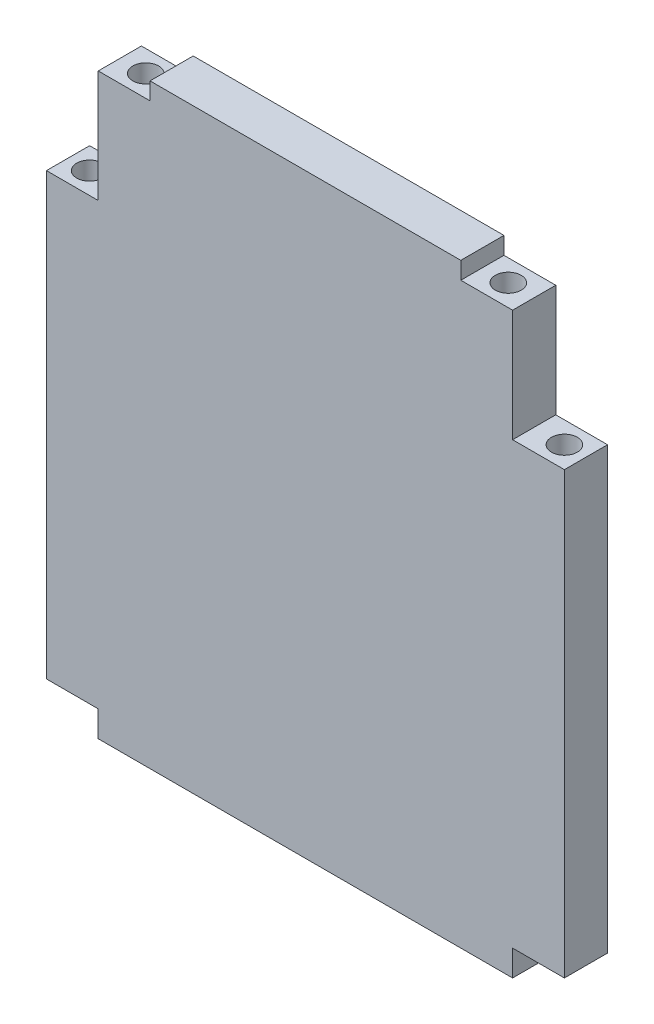
SolidWorks part; units mm, degrees
material "5052-O"
ref_plane "正面" through (0, 0, 0) normal (0, 0, 1) x (1, 0, 0)
ref_plane "平面" through (0, 0, 0) normal (0, 1, 0) x (1, 0, 0)
ref_plane "右側面" through (0, 0, 0) normal (1, 0, 0) x (0, 0, -1)
sketch "ｽｹｯﾁ1" plane through (0, 0, 0) normal (0, 0, 1) x (1, 0, 0)
  line L0 (-30, 0) -> (30, 0) construction
  line L1 (30, -25.5) -> (-30, -25.5) construction
  line L2 (30, -25.5) -> (30, 25.5)
  line L3 (30, 25.5) -> (-30, 25.5) construction
  line L4 (-30, -25.5) -> (-30, 25.5)
  line L5 (30, -25.5) -> (-30, 25.5) construction
  line L6 (30, 25.5) -> (-30, -25.5) construction
  line L7 (-30, 25.5) -> (-24, 25.5)
  line L8 (-24, 25.5) -> (-24, 38.5)
  line L9 (-24, 38.5) -> (-18, 38.5)
  line L10 (24, 38.5) -> (24, 25.5)
  line L11 (24, 25.5) -> (30, 25.5)
  line L12 (-30, -25.5) -> (-24, -25.5)
  line L13 (-24, -25.5) -> (-24, -28.5)
  line L14 (-24, -28.5) -> (24, -28.5)
  line L15 (24, -28.5) -> (24, -25.5)
  line L16 (24, -25.5) -> (30, -25.5)
  line L17 (-18, 38.5) -> (-18, 40.5)
  line L18 (-18, 40.5) -> (18, 40.5)
  line L19 (18, 40.5) -> (18, 38.5)
  line L20 (18, 38.5) -> (24, 38.5)
  point P0 (0, 0)
  dimension "D1" = 60
  dimension "D2" = 51
  dimension "D3" = 13
  dimension "D4" = 6
  dimension "D5" = 3
  dimension "D6" = 2
extrude "ﾎﾞｽ - 押し出し1" add sketch "ｽｹｯﾁ1" along normal blind 5
sketch "ｽｹｯﾁ2" plane through (0, 25.5, 0) normal (0, 1, 0) x (1, 0, 0)
  line L0 (-30, -2.5) -> (30, -2.5) construction
  line L1 (-30, -5) -> (-30, 0) construction
  line L2 (30, -5) -> (30, 0) construction
  line L3 (18, -5) -> (-18, -5) construction
  line L4 (0, 0) -> (0, -5) construction
  circle A0 centre (-27.5, -2.5) radius 1.5
  circle A1 centre (27.5, -2.5) radius 1.5
  dimension "D1" = 2.5
  dimension "D2" = 3
extrude "ｶｯﾄ - 押し出し1" cut sketch "ｽｹｯﾁ2" against normal blind 10
mirror "ﾐﾗｰ1" about plane through (0, 0, 0) normal (0, 1, 0) of "ｶｯﾄ - 押し出し1"
sketch "ｽｹｯﾁ3" plane through (0, 38.5, 0) normal (0, 1, 0) x (1, 0, 0)
  line L0 (-24, 0) -> (-18, -5) construction
  line L2 (18, 0) -> (-18, 0) construction
  line L3 (0, 0) -> (0, -5) construction
  line L4 (18, -5) -> (-18, -5) construction
  circle A0 centre (-21, -2.5) radius 1.5
  circle A1 centre (-27.5, -2.5) radius 1.5 construction
  circle A2 centre (21, -2.5) radius 1.5
extrude "ｶｯﾄ - 押し出し2" cut sketch "ｽｹｯﾁ3" against normal blind 10
